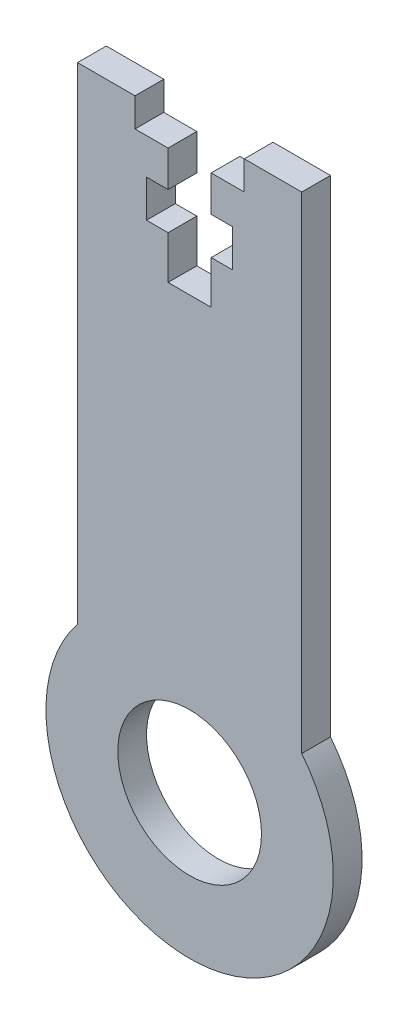
SolidWorks part; units mm, degrees
ref_plane "前视基准面" through (0, 0, 0) normal (0, 0, 1) x (1, 0, 0)
ref_plane "上视基准面" through (0, 0, 0) normal (0, 1, 0) x (1, 0, 0)
ref_plane "右视基准面" through (0, 0, 0) normal (1, 0, 0) x (0, 0, -1)
sketch "草图1" plane through (0, 0, 0) normal (0, 0, 1) x (1, 0, 0)
  line L12 (0.7531, 26.8576) -> (3.0531, 26.8576)
  line L24 (-4.5469, 28.8576) -> (-8.5469, 28.8576)
  line L25 (-4.5469, 26.8576) -> (-2.2469, 26.8576)
  line L28 (-4.5469, 28.8576) -> (-4.5469, 26.8576)
  line L30 (-3.7469, 24.3576) -> (-3.7469, 21.7576)
  line L31 (-3.7469, 21.7576) -> (-2.2469, 21.7576)
  line L32 (-2.2469, 21.7576) -> (-2.2469, 18.7576)
  line L33 (0.7531, 21.7576) -> (0.7531, 18.7576)
  line L34 (2.2531, 21.7576) -> (0.7531, 21.7576)
  line L35 (2.2531, 24.3576) -> (2.2531, 21.7576)
  line L36 (-2.2469, 24.3576) -> (-3.7469, 24.3576)
  line L37 (-2.2469, 18.7576) -> (0.7531, 18.7576)
  line L38 (0.7531, 24.3576) -> (2.2531, 24.3576)
  line L39 (-2.2469, 24.3576) -> (-2.2469, 26.8576)
  line L40 (0.7531, 24.3576) -> (0.7531, 26.8576)
  line L56 (-8.5469, 28.8576) -> (-8.5469, -4.9846)
  line L60 (3.0531, 26.8576) -> (3.0531, 28.8576)
  line L61 (3.0531, 28.8576) -> (7.0531, 28.8576)
  line L64 (-0.7469, -11.2424) -> (-0.7469, 18.7576) construction
  line L65 (7.0531, -4.9846) -> (7.0531, 28.8576)
  circle A0 centre (-0.7469, -11.2424) radius 5
  circle A1 centre (-0.7469, -11.2424) radius 10 construction
  arc A2 (7.0531, -4.9846) -> (-8.5469, -4.9846) centre (-0.7469, -11.2424) cw
extrude "凸台-拉伸1" add sketch "草图1" along normal blind 2
sketch "草图2" plane through (0, 26.8576, 0) normal (0, 1, 0) x (1, 0, 0)
  line L0 (-2.2469, -1) -> (0.7531, -1)
  line L1 (-2.2469, -2) -> (-2.2469, 0) construction
  line L2 (0.7531, -2) -> (0.7531, 0) construction
  circle A0 centre (-0.7469, -1) radius 1.5
